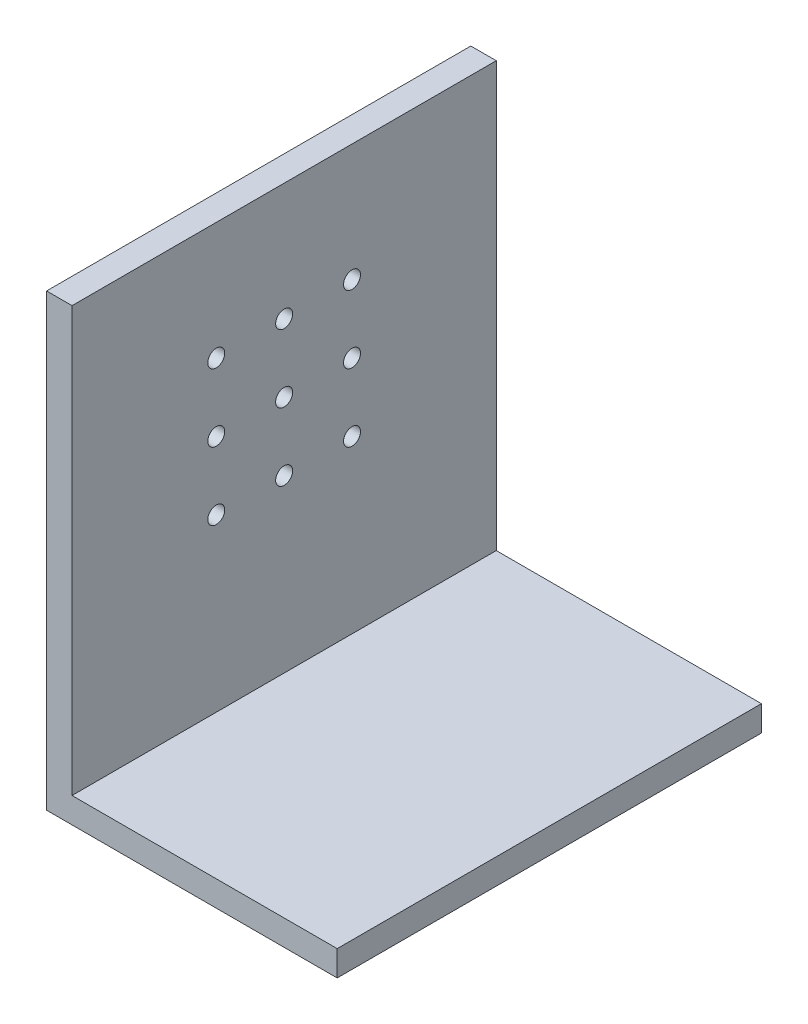
SolidWorks part; units mm, degrees
ref_plane "前视基准面" through (0, 0, 0) normal (0, 0, 1) x (1, 0, 0)
ref_plane "上视基准面" through (0, 0, 0) normal (0, 1, 0) x (1, 0, 0)
ref_plane "右视基准面" through (0, 0, 0) normal (1, 0, 0) x (0, 0, -1)
sketch "草图1" plane through (0, 0, 0) normal (0, 1, 0) x (1, 0, 0)
  line L0 (-30.6851, 0) -> (48.5987, 0) construction
  line L1 (0, 25) -> (34.2512, 25)
  line L2 (0, 25) -> (0, -25)
  line L3 (0, -25) -> (34.2512, -25)
  line L4 (34.2512, 25) -> (34.2512, -25)
  point P7 (0, 0)
  dimension "D1" = 50
extrude "凸台-拉伸1" add sketch "草图1" along normal blind 3
sketch "草图2" plane through (0, 3, 0) normal (0, 1, 0) x (1, 0, 0)
  line L0 (0, -25) -> (34.2512, -25) construction
  line L1 (0, 25) -> (3, 25)
  line L2 (0, 25) -> (0, -25)
  line L3 (0, -25) -> (3, -25)
  line L4 (3, 25) -> (3, -25)
  dimension "D1" = 3
extrude "凸台-拉伸2" add sketch "草图2" along normal blind 50
sketch "草图3" plane through (0, 0, 0) normal (-1, 0, 0) x (0, 0, 1)
  line L0 (0, -10.0931) -> (0, 65.4065) construction
  circle A0 centre (-8, 39.1561) radius 1
  point P5 (0, 0)
  dimension "D2" = 2
  dimension "D1" = 8
extrude "切除-拉伸1" cut sketch "草图3" against normal blind 50
pattern_linear "阵列(线性)1" count 3 spacing 8 along (0, 0, 1) of "切除-拉伸1"
pattern_linear "阵列(线性)2" count 3 spacing 8 along (0, -1, 0) of "阵列(线性)1", "切除-拉伸1"
